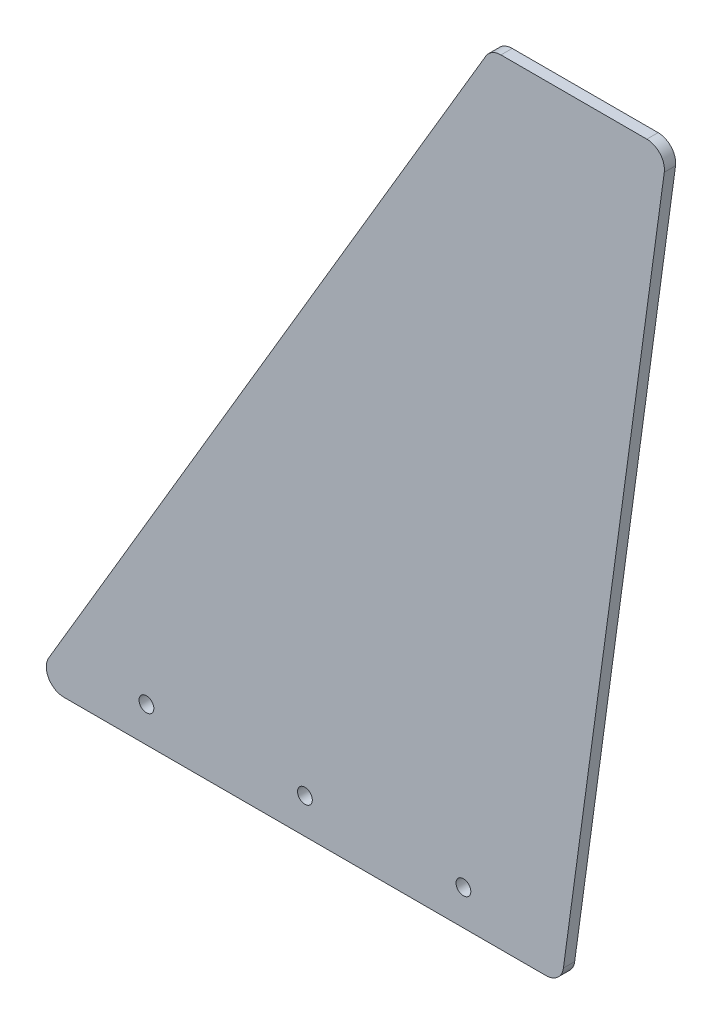
SolidWorks part; units mm, degrees
ref_plane "Спереди" through (0, 0, 0) normal (0, 0, 1) x (1, 0, 0)
ref_plane "Сверху" through (0, 0, 0) normal (0, 1, 0) x (1, 0, 0)
ref_plane "Справа" through (0, 0, 0) normal (1, 0, 0) x (0, 0, -1)
other "Configuration Table"
sketch "Эскиз1" plane through (0, 0, 0) normal (0, 0, 1) x (1, 0, 0)
  line L0 (0, 0) -> (150, 0)
  line L1 (150, 0) -> (180, 220)
  line L2 (180, 220) -> (130, 220)
  line L3 (130, 220) -> (0, 0)
  line L4 (130, 220) -> (130, 20) construction
  line L12 (130, 10) -> (130, 0) construction
  point P8 (0, 0)
  dimension "D1" = 150
  dimension "D2" = 220
  dimension "D3" = 130
extrude "Бобышка-Вытянуть1" add sketch "Эскиз1" along normal blind 3.2
fillet "Скругление1" radius 5 4 edges at (0, 0, 1.6) (150, 0, 1.6) (180, 220, 1.6) (130, 220, 1.6)
sketch "Эскиз2" plane through (0, 0, 3.2) normal (0, 0, 1) x (1, 0, 0)
  line L0 (77.1989, 0) -> (77.1989, 20) construction
  line L1 (8.7622, 0) -> (145.6355, 0) construction
  line L2 (23.4336, 20) -> (142.6347, 20) construction
  circle A0 centre (77.1989, 10) radius 2.1
  dimension "D1" = 4.2
  dimension "D2" = 10
extrude "Вырез-Вытянуть1" cut sketch "Эскиз2" against normal blind 3.2
pattern_linear "Линейный массив1" count 2 spacing 45 along (1, 0, 0) count 2 spacing 45 along (-1, 0, 0) of "Вырез-Вытянуть1"
sketch "Эскиз3" plane through (0, 0, 0) normal (0, 0, 1) x (1, 0, 0)
  line L1 (135.7063, 210) -> (23.4336, 20) construction
  line L2 (142.6347, 20) -> (168.5438, 210) construction
  line L6 (70.7063, 100) -> (107.1251, 100)
  line L7 (153.5438, 100) -> (154.9075, 110)
  line L8 (154.9075, 110) -> (120.7614, 110)
  line L9 (76.6154, 110) -> (70.7063, 100)
  line L10 (152.1251, 210) -> (83.0342, 20) construction
  line L11 (168.5438, 210) -> (135.7063, 210) construction
  line L12 (23.4336, 20) -> (142.6347, 20) construction
  line L17 (147.1251, 210) -> (110.7614, 110)
  line L18 (78.0342, 20) -> (88.0342, 20)
  line L19 (88.0342, 20) -> (117.1251, 100)
  line L20 (147.1251, 210) -> (157.1251, 210)
  line L21 (120.7614, 110) -> (157.1251, 210)
  line L22 (110.7614, 110) -> (76.6154, 110)
  line L23 (107.1251, 100) -> (78.0342, 20)
  line L24 (117.1251, 100) -> (153.5438, 100)
  dimension "D1" = 100
  dimension "D2" = 10
  dimension "D7" = 10
  dimension "D8" = 5
sketch "Эскиз4" plane through (0, 0, 0) normal (0, 0, 1) x (1, 0, 0)
  line L0 (38.2063, 45) -> (63.2063, 45)
  line L1 (135.7063, 210) -> (23.4336, 20) construction
  line L2 (142.6347, 20) -> (168.5438, 210) construction
  line L3 (146.0438, 45) -> (147.4075, 55)
  line L4 (147.4075, 55) -> (100.7614, 55)
  line L5 (44.1154, 55) -> (38.2063, 45)
  line L6 (23.4336, 20) -> (142.6347, 20) construction
  line L7 (38.2063, 45) -> (38.2063, 20)
  line L8 (152.1251, 210) -> (83.0342, 20) construction
  line L9 (63.2063, 20) -> (63.2063, 45)
  line L10 (73.2063, 45) -> (73.2063, 20)
  line L11 (38.2063, 45) -> (23.4336, 20)
  line L12 (23.4336, 20) -> (38.2063, 20)
  line L13 (73.2063, 45) -> (146.0438, 45)
  line L14 (73.2063, 20) -> (63.2063, 20)
  line L15 (168.5438, 210) -> (135.7063, 210) construction
  line L16 (23.4336, 20) -> (142.6347, 20) construction
  line L17 (157.1251, 210) -> (128.216, 130.5)
  line L18 (147.1251, 210) -> (157.1251, 210)
  line L19 (90.7614, 55) -> (114.5796, 120.5)
  line L20 (82.8199, 120.5) -> (114.5796, 120.5)
  line L21 (135.7063, 210) -> (23.4336, 20) construction
  line L22 (142.6347, 20) -> (168.5438, 210) construction
  line L23 (156.3393, 120.5) -> (157.7029, 130.5)
  line L24 (157.7029, 130.5) -> (128.216, 130.5)
  line L25 (88.729, 130.5) -> (82.8199, 120.5)
  line L26 (124.5796, 120.5) -> (100.7614, 55)
  line L27 (118.216, 130.5) -> (88.729, 130.5)
  line L28 (118.216, 130.5) -> (147.1251, 210)
  line L29 (124.5796, 120.5) -> (156.3393, 120.5)
  line L30 (90.7614, 55) -> (44.1154, 55)
  dimension "D1" = 10
  dimension "D2" = 25
  dimension "D3" = 25
  dimension "D4" = 10
  dimension "D5" = 5
  dimension "D6" = 10
  dimension "D7" = 10
  dimension "D8" = 65.5
